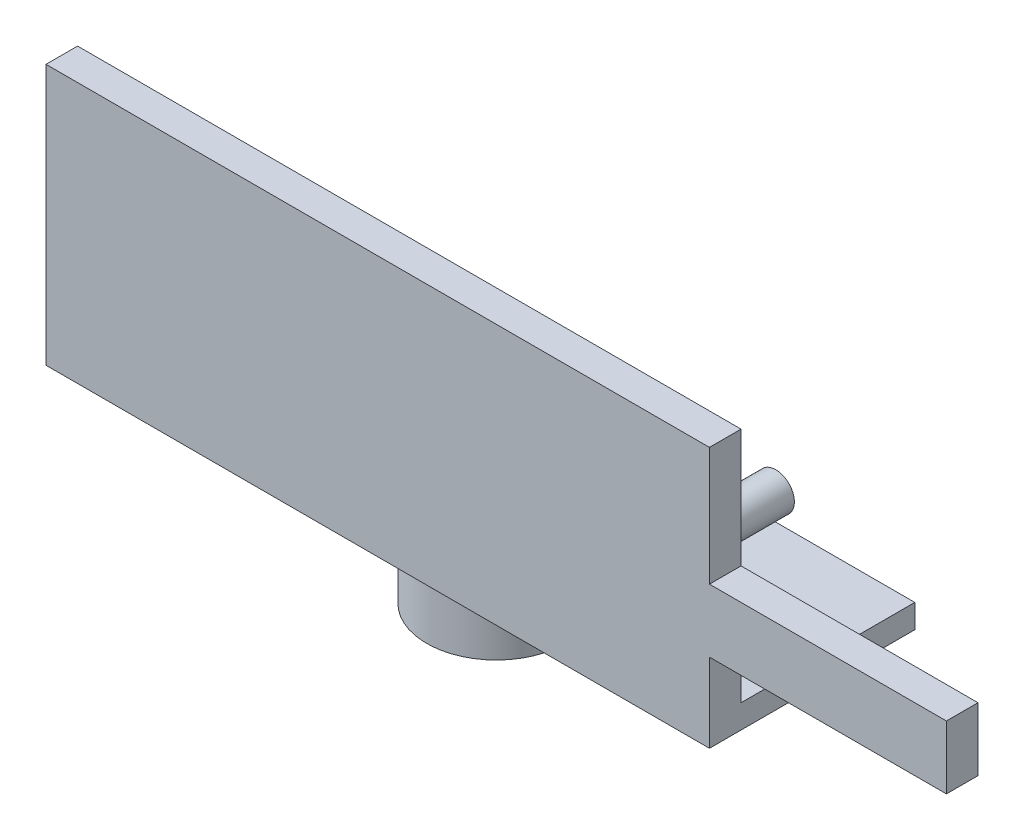
SolidWorks part; units mm, degrees
ref_plane "Plan de face" through (0, 0, 0) normal (0, 0, 1) x (1, 0, 0)
ref_plane "Plan de dessus" through (0, 0, 0) normal (0, 1, 0) x (1, 0, 0)
ref_plane "Plan de droite" through (0, 0, 0) normal (1, 0, 0) x (0, 0, -1)
sketch "Esquisse1" plane through (0, 0, 0) normal (0, 0, 1) x (1, 0, 0)
  line L1 (0, 0) -> (42, 0)
  line L2 (0, 0) -> (0, 15)
  line L3 (0, 15) -> (42, 15)
  line L4 (42, 0) -> (42, 15)
  dimension "D1" = 42
  dimension "D2" = 15
extrude "Boss.-Extru.1" add sketch "Esquisse1" along normal blind 2
sketch "Esquisse2" plane through (0, 0, 0) normal (0, 0, -1) x (-1, 0, 0)
  line L0 (-21, 0) -> (-21, 15) construction
  line L1 (0, 0) -> (-42, 0) construction
  line L2 (-42, 15) -> (0, 15) construction
  circle A0 centre (-39, 7.5) radius 1.175
  circle A1 centre (-3, 7.5) radius 1.175
  dimension "D3" = 2.35
  dimension "D1" = 7.5
  dimension "D2" = 18
extrude "Boss.-Extru.2" add sketch "Esquisse2" along normal blind 5.2
sketch "Esquisse3" plane through (42, 0, 0) normal (1, 0, 0) x (0, 0, -1)
  line L0 (-2, 0) -> (-2, 15) construction
  line L1 (-2, 3.5) -> (0, 3.5)
  line L2 (-2, 3.5) -> (-2, 7.5)
  line L3 (-2, 7.5) -> (0, 7.5)
  line L4 (0, 3.5) -> (0, 7.5)
  line L5 (0, 0) -> (0, 15) construction
  line L6 (-2, 15) -> (0, 15) construction
  dimension "D1" = 4
  dimension "D2" = 7.5
extrude "Boss.-Extru.3" add sketch "Esquisse3" along normal blind 15
sketch "Esquisse4" plane through (0, 0, 0) normal (0, -1, 0) x (1, 0, 0)
  line L4 (0, 0) -> (42, 0)
  line L5 (42, 0) -> (42, 2)
  line L6 (42, 2) -> (0, 2)
  line L7 (0, 2) -> (0, 0)
  line L8 (0, 0) -> (42, 0)
  line L9 (42, 0) -> (42, 2)
  line L10 (42, 2) -> (0, 2)
  line L11 (0, 2) -> (0, 0)
  dimension "D1" = 0
extrude "Boss.-Extru.4" add sketch "Esquisse4" along normal blind 1.5
sketch "Esquisse5" plane through (0, 0, 0) normal (0, 0, -1) x (-1, 0, 0)
  line L1 (-42, -1.5) -> (0, -1.5)
  line L2 (-42, -1.5) -> (-42, 0)
  line L3 (-42, 0) -> (0, 0)
  line L4 (0, -1.5) -> (0, 0)
extrude "Boss.-Extru.5" add sketch "Esquisse5" along normal blind 11
sketch "Esquisse6" plane through (0, -1.5, 0) normal (0, -1, 0) x (1, 0, 0)
  line L0 (42, -11) -> (0, -11) construction
  line L2 (42, -11) -> (42, 2) construction
  line L4 (19.0021, -7.0027) -> (22.9979, -7.0027)
  line L6 (18.9979, -4.0027) -> (23.0021, -4.0027)
  arc A0 (18.9979, -4.0027) -> (19.0021, -7.0027) centre (21, -5.5) ccw
  circle A1 centre (21, -5.5) radius 4.4024
  arc A2 (22.9979, -7.0027) -> (23.0021, -4.0027) centre (21, -5.5) ccw
  dimension "D4" = 5
  dimension "D1" = 5.5
  dimension "D2" = 21
extrude "Boss.-Extru.6" add sketch "Esquisse6" along normal blind 6.3
